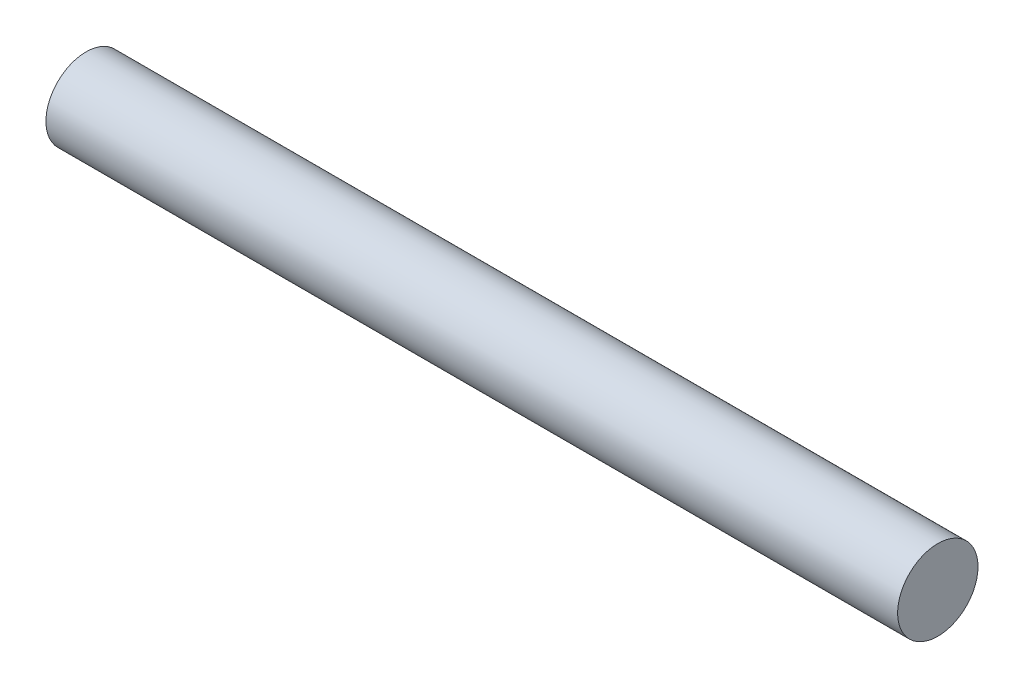
SolidWorks part; units mm, degrees
ref_plane "Front Plane" through (0, 0, 0) normal (0, 0, 1) x (1, 0, 0)
ref_plane "Top Plane" through (0, 0, 0) normal (0, 1, 0) x (1, 0, 0)
ref_plane "Right Plane" through (0, 0, 0) normal (1, 0, 0) x (0, 0, -1)
sketch "Sketch1" plane through (0, 0, 0) normal (1, 0, 0) x (0, 0, -1)
  circle A0 centre (0, 0) radius 2.5
  dimension "D1" = 5
extrude "Boss-Extrude1" add sketch "Sketch1" along normal blind 53
